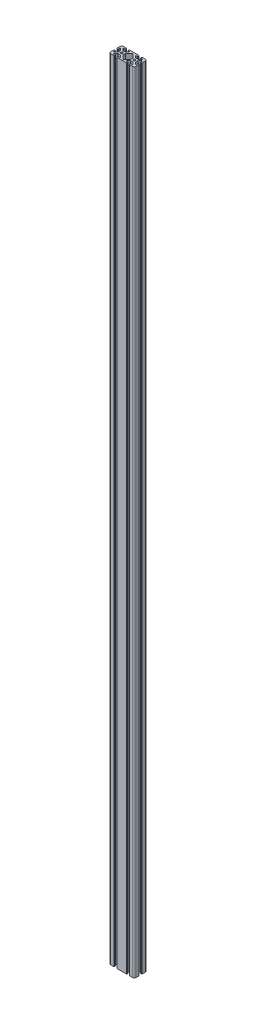
SolidWorks part; units mm, degrees
material "4032-T6"
ref_plane "Front Plane" through (0, 0, 0) normal (0, 0, 1) x (1, 0, 0)
ref_plane "Top Plane" through (0, 0, 0) normal (0, 1, 0) x (1, 0, 0)
ref_plane "Right Plane" through (0, 0, 0) normal (1, 0, 0) x (0, 0, -1)
sketch "Sketch1" plane through (0, 0, 0) normal (0, 1, 0) x (1, 0, 0)
  line L1 (5, 0) -> (75, 0)
  line L2 (0, -5) -> (0, -35)
  line L3 (5, -40) -> (75, -40)
  line L4 (80, -5) -> (80, -35)
  arc A0 (75, -40) -> (80, -35) centre (75, -35) ccw
  arc A1 (80, -5) -> (75, 0) centre (75, -5) ccw
  arc A2 (5, -40) -> (0, -35) centre (5, -35) cw
  arc A3 (0, -5) -> (5, 0) centre (5, -5) cw
  point P7 (80, -40)
  point P10 (80, 0)
  point P15 (0, 0)
  dimension "D3" = 5
  dimension "D1" = 80
  dimension "D2" = 40
extrude "Boss-Extrude1" add sketch "Sketch1" along normal blind 2500 contours L3 A0 L4 A1 L1 A3 L2 A2
sketch "Sketch3" plane through (0, 2500, 0) normal (0, 1, 0) x (1, 0, 0)
  line L0 (40, -2.5254) -> (40, -32.3671)
  line L1 (0, -5) -> (0, -35) construction
  line L2 (5, 0) -> (75, 0) construction
  circle A0 centre (20, -20) radius 3.4
  dimension "D4" = 6.8
  dimension "D1" = 40
  dimension "D2" = 20
  dimension "D3" = 20
extrude "Cut-Extrude1" cut sketch "Sketch3" against normal through all contours A0
ref_plane "mirro-plane" through (40, 0, 0) normal (1, 0, 0) x (0, 0, -1)
mirror "Mirror3" about plane through (40, 0, 0) normal (1, 0, 0) of "Cut-Extrude1"
ref_plane "sk5mirrorPlane" through (0, 0, 20) normal (0, 0, 1) x (1, 0, 0)
sketch "Sketch7" plane through (0, 0, 0) normal (0, -1, 0) x (-1, 0, 0)
  line L2 (-5, -40) -> (-75, -40) construction
  line L4 (-15.9, -40) -> (-24.1, -40)
  line L8 (-15.9, -40) -> (-15.9, -36.5)
  line L12 (-16.3092, -27.8) -> (-23.6908, -27.8)
  line L23 (-10.5103, -35.5) -> (-14.9, -35.5)
  line L25 (-24.1, -40) -> (-24.1, -36.5)
  line L27 (-15.6082, -28.0868) -> (-9.8093, -33.7868)
  line L31 (-29.4898, -35.5) -> (-25.1, -35.5)
  line L43 (-24.3918, -28.0868) -> (-30.1908, -33.7868)
  arc A0 (-24.3918, -28.0868) -> (-23.6908, -27.8) centre (-23.6908, -28.8) cw
  arc A1 (-16.3092, -27.8) -> (-15.6082, -28.0868) centre (-16.3092, -28.8) cw
  arc A2 (-30.1908, -33.7868) -> (-29.4898, -35.5) centre (-29.4898, -34.5) ccw
  arc A3 (-9.8093, -33.7868) -> (-10.5103, -35.5) centre (-10.5103, -34.5) cw
  arc A4 (-25.1, -35.5) -> (-24.1, -36.5) centre (-25.1, -36.5) cw
  arc A5 (-14.9, -35.5) -> (-15.9, -36.5) centre (-14.9, -36.5) ccw
  point P96 (-24.1, -35.5)
  dimension "D17" = 0
  dimension "D18" = 1
  dimension "D8" = 12.2
extrude "Cut-Extrude2" cut sketch "Sketch7" against normal through all
fillet "Fillet1" radius 1 2 edges at (15.9, 1250, 40) (24.1, 1250, 40)
mirror "Mirror8" about plane through (40, 0, 0) normal (1, 0, 0) of "Cut-Extrude2"
fillet "Fillet2" radius 1 1 edges at (55.9, 1250, 40)
fillet "Fillet3" radius 1 1 edges at (64.1, 1250, 40)
sketch "Sketch9" plane through (0, 0, 0) normal (0, 1, 0) x (1, 0, 0)
  line L1 (14.8998, -4.5007) -> (10.4505, -4.5007)
  line L3 (24.0998, -3.5) -> (24.1, 0)
  line L4 (15.8998, -3.5008) -> (15.9, 0)
  line L5 (15.9, 0) -> (24.1, 0)
  line L6 (16.1497, -12.2) -> (23.8503, -12.2)
  line L7 (5, 0) -> (75, 0) construction
  line L8 (25.0998, -4.5) -> (29.5503, -4.5)
  line L12 (9.7434, -6.2078) -> (15.4426, -11.9071)
  line L16 (24.5574, -11.9071) -> (30.2574, -6.2071)
  arc A0 (15.8998, -3.5008) -> (14.8998, -4.5007) centre (14.8998, -3.5007) cw
  arc A1 (24.0998, -3.5) -> (25.0998, -4.5) centre (25.0998, -3.5) ccw
  arc A2 (29.5503, -4.5) -> (30.2574, -6.2071) centre (29.5503, -5.5) cw
  arc A3 (24.5574, -11.9071) -> (23.8503, -12.2) centre (23.8503, -11.2) cw
  arc A4 (9.7434, -6.2078) -> (10.4505, -4.5007) centre (10.4505, -5.5007) cw
  arc A5 (15.4426, -11.9071) -> (16.1497, -12.2) centre (16.1497, -11.2) ccw
  dimension "D2" = 1
  dimension "D1" = 0
  dimension "D5" = 12.2
  dimension "D6" = 4.5
extrude "Cut-Extrude3" cut sketch "Sketch9" along normal through all
mirror "Mirror9" about plane through (40, 0, 0) normal (1, 0, 0) of "Cut-Extrude3"
sketch "Sketch10" plane through (0, 0, 0) normal (0, 1, 0) x (1, 0, 0)
  line L0 (4.5, -14.9) -> (4.5, -10.5861)
  line L4 (0, -24.1) -> (3.5, -24.1)
  line L5 (0, -15.9) -> (3.5, -15.9)
  line L8 (12.2, -23.4919) -> (12.2, -16.5081)
  line L10 (0, -5) -> (0, -35) construction
  line L13 (4.5, -29.4139) -> (4.5, -25.1)
  line L25 (11.9205, -24.1853) -> (6.2205, -30.1074)
  line L26 (11.9205, -15.8147) -> (6.2205, -9.8926)
  line L29 (0, -24.1) -> (0, -15.9)
  arc A0 (4.5, -14.9) -> (3.5, -15.9) centre (3.5, -14.9) cw
  arc A1 (3.5, -24.1) -> (4.5, -25.1) centre (3.5, -25.1) cw
  arc A2 (6.2205, -9.8926) -> (4.5, -10.5861) centre (5.5, -10.5861) ccw
  arc A3 (11.9205, -15.8147) -> (12.2, -16.5081) centre (11.2, -16.5081) cw
  arc A4 (11.9205, -24.1853) -> (12.2, -23.4919) centre (11.2, -23.4919) ccw
  arc A5 (4.5, -29.4139) -> (6.2205, -30.1074) centre (5.5, -29.4139) ccw
  dimension "D3" = 1
  dimension "D7" = 12.2
  dimension "D9" = 4.5
  dimension "D17" = 0
extrude "Cut-Extrude4" cut sketch "Sketch10" along normal through all
fillet "Fillet4" radius 1 1 edges at (24.1, 1250, 0)
fillet "Fillet5" radius 1 1 edges at (64.1, 1250, 0)
fillet "Fillet6" radius 1 1 edges at (55.9, 1250, 0)
fillet "Fillet7" radius 1 1 edges at (15.9, 1250, 0)
fillet "Fillet8" radius 1 1 edges at (0, 1250, 24.1)
fillet "Fillet9" radius 1 1 edges at (0, 1250, 15.9)
sketch "Sketch11" plane through (0, 0, 0) normal (0, 1, 0) x (1, 0, 0)
  line L0 (75.5, -29.6797) -> (75.5, -25.1)
  line L1 (80, -5) -> (80, -35) construction
  line L2 (67.5, -16.0953) -> (67.5, -23.9047)
  line L5 (75.5, -14.9) -> (75.5, -10.3203)
  line L7 (80, -24.1) -> (80, -15.9)
  line L8 (80, -5) -> (80, -35) construction
  line L13 (113.5168, -27.8) -> (113.5178, -27.6385)
  line L17 (67.8065, -15.3748) -> (73.8065, -9.5998)
  line L63 (67.8065, -24.6252) -> (73.8065, -30.4002)
  line L66 (76.5, -15.9) -> (80, -15.9)
  line L68 (76.5, -24.1) -> (80, -24.1)
  arc A44 (75.5, -25.1) -> (76.5, -24.1) centre (76.5, -25.1) cw
  arc A45 (75.5, -14.9) -> (76.5, -15.9) centre (76.5, -14.9) ccw
  arc A46 (73.8065, -9.5998) -> (75.5, -10.3203) centre (74.5, -10.3203) cw
  arc A47 (73.8065, -30.4002) -> (75.5, -29.6797) centre (74.5, -29.6797) ccw
  arc A48 (67.8065, -24.6252) -> (67.5, -23.9047) centre (68.5, -23.9047) cw
  arc A49 (67.8065, -15.3748) -> (67.5, -16.0953) centre (68.5, -16.0953) ccw
  dimension "D3" = 1
  dimension "D2" = 4.5
  dimension "D4" = 12.5
ref_plane "offset1" through (60, 0, 0) normal (1, 0, 0) x (0, 0, -1)
mirror "Mirror10" about plane through (40, 0, 0) normal (1, 0, 0) of "Cut-Extrude4"
fillet "Fillet10" radius 1 1 edges at (80, 1250, 15.9)
fillet "Fillet11" radius 1 1 edges at (80, 1250, 24.1)
mirror "Mirror11" about plane through (60, 0, 0) normal (1, 0, 0) of "Mirror10"
ref_plane "Plane2" through (20, 0, 0) normal (-1, 0, 0) x (0, 0, 1)
mirror "Mirror12" about plane through (20, 0, 0) normal (-1, 0, 0) of "Cut-Extrude4"
sketch "Sketch12" plane through (0, 0, 0) normal (0, -1, 0) x (-1, 0, 0)
  line L0 (-28.0795, -24.1853) -> (-39.3271, -35.8711)
  line L2 (-51.9226, -24.2109) -> (-40.7702, -35.8689)
  line L4 (-39.2795, -4.1783) -> (-28.0795, -15.8147)
  line L7 (-51.9205, -15.8147) -> (-40.7205, -4.1783)
  line L8 (-27.8, -23.4919) -> (-27.8, -16.5081)
  line L9 (-52.2, -23.5196) -> (-52.2, -16.5081)
  line L10 (-52.2, -23.4919) -> (-52.2, -16.5081) construction
  line L11 (-27.8, -23.4919) -> (-27.8, -16.5081) construction
  arc A0 (-39.2795, -4.1783) -> (-40.7205, -4.1783) centre (-40, -4.8718) ccw
  arc A1 (-39.3271, -35.8711) -> (-40.7702, -35.8689) centre (-40.0476, -35.1776) cw
  arc A2 (-51.9205, -15.8147) -> (-52.2, -16.5081) centre (-51.2, -16.5081) ccw
  arc A3 (-52.2, -23.5196) -> (-51.9226, -24.2109) centre (-51.2, -23.5196) ccw
  arc A4 (-28.0795, -15.8147) -> (-27.8, -16.5081) centre (-28.8, -16.5081) cw
  arc A5 (-27.8, -23.4919) -> (-28.0795, -24.1853) centre (-28.8, -23.4919) cw
  dimension "D3" = 1
  dimension "D4" = 1
  dimension "D1" = 0
  dimension "D2" = 0
extrude "Cut-Extrude5" cut sketch "Sketch12" against normal through all
